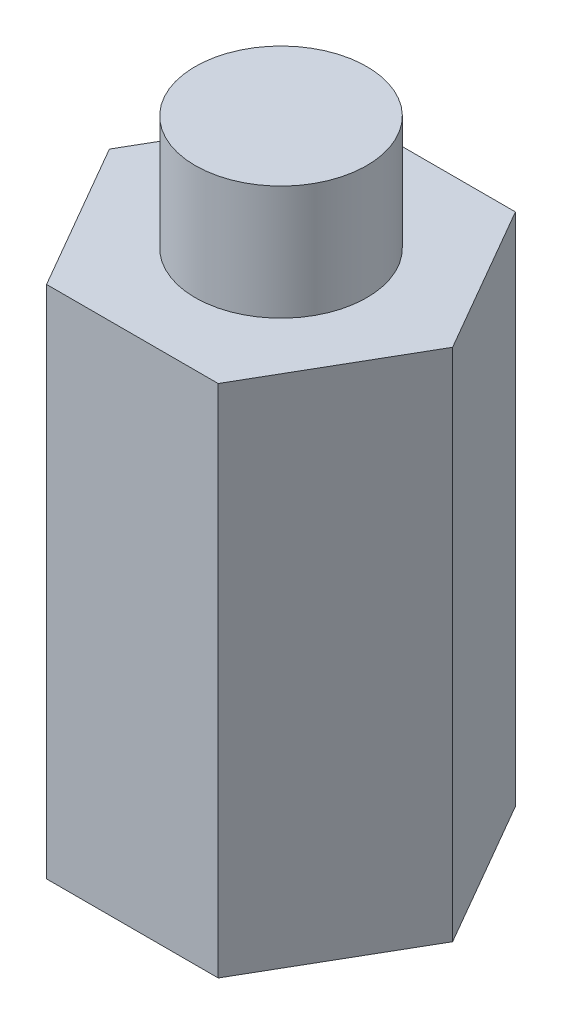
SolidWorks part; units mm, degrees
ref_plane "前视基准面" through (0, 0, 0) normal (0, 0, 1) x (1, 0, 0)
ref_plane "上视基准面" through (0, 0, 0) normal (0, 1, 0) x (1, 0, 0)
ref_plane "右视基准面" through (0, 0, 0) normal (1, 0, 0) x (0, 0, -1)
other "Configuration Table"
sketch "草图1" plane through (0, 0, 0) normal (0, 1, 0) x (1, 0, 0)
  line L1 (3, 0) -> (1.5, 2.5981)
  line L2 (1.5, 2.5981) -> (-1.5, 2.5981)
  line L3 (-1.5, 2.5981) -> (-3, 0)
  line L4 (-3, 0) -> (-1.5, -2.5981)
  line L5 (-1.5, -2.5981) -> (1.5, -2.5981)
  line L6 (1.5, -2.5981) -> (3, 0)
  circle A0 centre (0, 0) radius 2.5981 construction
  circle A1 centre (0, 0) radius 1.5
  dimension "D2" = 3
  dimension "D1" = 3
extrude "凸台-拉伸1" add sketch "草图1" along normal blind 9
sketch "草图2" plane through (0, 9, 0) normal (0, 1, 0) x (1, 0, 0)
  circle A0 centre (0, 0) radius 1.5
  dimension "D1" = 3
extrude "凸台-拉伸2" add sketch "草图2" along normal blind 2 and the other way blind 1 contours A0
